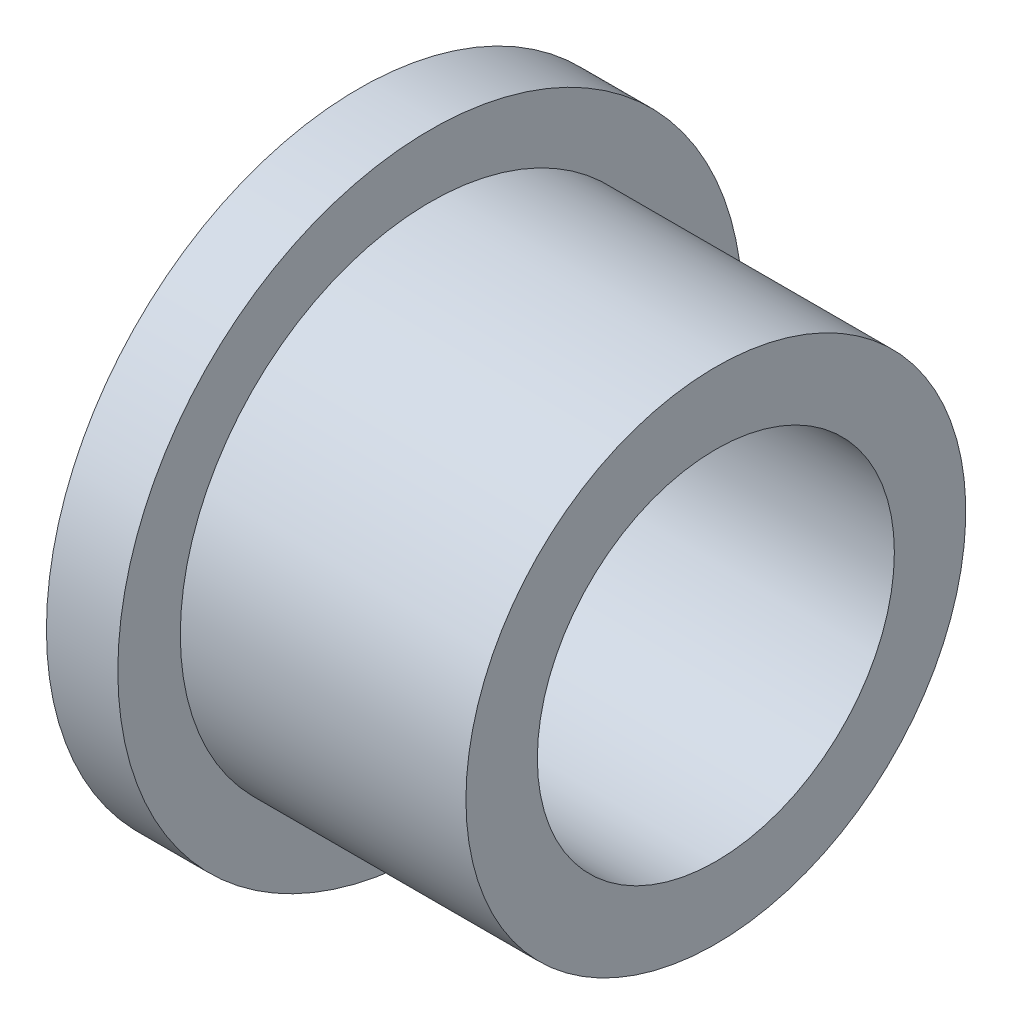
SolidWorks part; units mm, degrees
material "Phosphor bronze 10% D, UNS C52400"
ref_plane "Front Plane" through (0, 0, 0) normal (0, 0, 1) x (1, 0, 0)
ref_plane "Top Plane" through (0, 0, 0) normal (0, 1, 0) x (1, 0, 0)
ref_plane "Right Plane" through (0, 0, 0) normal (1, 0, 0) x (0, 0, -1)
sketch "Sketch1" plane through (0, 0, 0) normal (0, 0, 1) x (1, 0, 0)
  line L0 (0, 10) -> (20, 10)
  line L1 (20, 10) -> (20, 14)
  line L2 (20, 14) -> (4, 14)
  line L3 (4, 14) -> (4, 17.5)
  line L4 (4, 17.5) -> (0, 17.5)
  line L5 (0, 17.5) -> (0, 10)
  line L6 (0, 0) -> (44.8454, 0) construction
  dimension "D1" = 20
  dimension "D2" = 4
  dimension "D3" = 35
  dimension "D4" = 20
  dimension "D5" = 28
revolve "Revolve1" add sketch "Sketch1" angle 360 about L6
